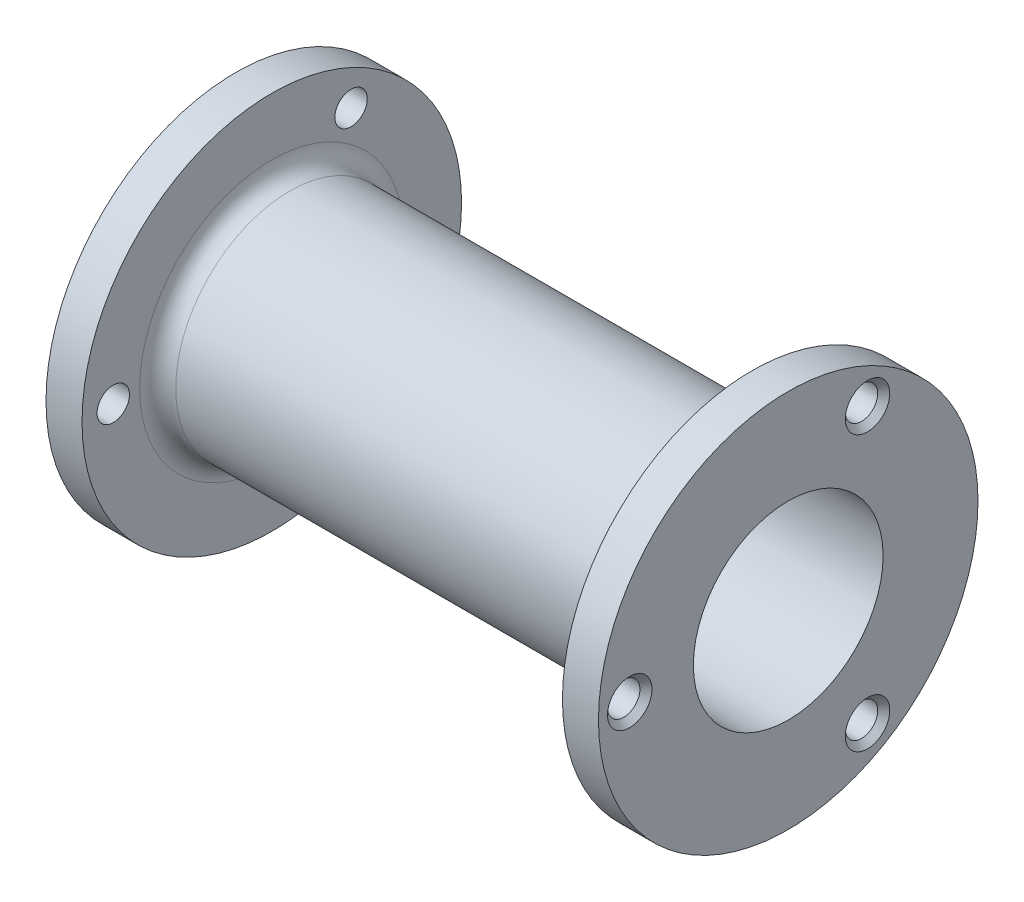
SolidWorks part; units mm, degrees
ref_plane "Front Plane" through (0, 0, 0) normal (0, 0, 1) x (1, 0, 0)
ref_plane "Top Plane" through (0, 0, 0) normal (0, 1, 0) x (1, 0, 0)
ref_plane "Right Plane" through (0, 0, 0) normal (1, 0, 0) x (0, 0, -1)
sketch "Sketch1" plane through (0, 0, 0) normal (0, 0, 1) x (1, 0, 0)
  line L0 (0, 7.9) -> (0, 15.8)
  line L1 (0, 0) -> (-13.4865, 0) construction
  line L2 (0, 15.8) -> (3, 15.8)
  line L3 (3, 15.8) -> (3, 11)
  line L4 (3, 7.9) -> (43, 7.9)
  line L5 (4.5, 9.5) -> (41.5, 9.5)
  line L6 (3, 7.9) -> (0, 7.9)
  line L7 (43, 11) -> (43, 15.8)
  line L8 (43, 15.8) -> (46, 15.8)
  line L9 (46, 15.8) -> (46, 7.9)
  line L10 (46, 7.9) -> (43, 7.9)
  arc A0 (41.5, 9.5) -> (43, 11) centre (41.5, 11) ccw
  arc A1 (4.5, 9.5) -> (3, 11) centre (4.5, 11) cw
  point P17 (3, 9.5)
  dimension "D1" = 15.8
  dimension "D2" = 3
  dimension "D6" = 1.5
  dimension "D3" = 31.6
  dimension "D4" = 1.6
  dimension "D5" = 40
revolve "Revolve1" add sketch "Sketch1" angle 360 about L1
sketch "Sketch3" plane through (46, 0, 0) normal (1, 0, 0) x (0, 0, -1)
  line L0 (-13.2, 0) -> (0, 0) construction
  circle A0 centre (-13.2, 0) radius 1.35
  circle A1 centre (0, 0) radius 15.8 construction
  circle A3 centre (6.6, 11.4315) radius 1.35
  circle A4 centre (6.6, -11.4315) radius 1.35
  point P4 (-15.8, 0)
  point P13 (0, 0)
  dimension "D1" = 13.2
  dimension "D2" = 2.7
  dimension "D3" = 3
extrude "Cut-Extrude1" cut sketch "Sketch3" against normal through all
chamfer "Chamfer1" distance 0.5 angle 45 6 edges at (46, 0, 11.85) (46, -11.4315, -7.95) (46, 11.4315, -7.95) (0, -11.4315, -7.95) (0, 11.4315, -7.95) (0, 0, 11.85)
